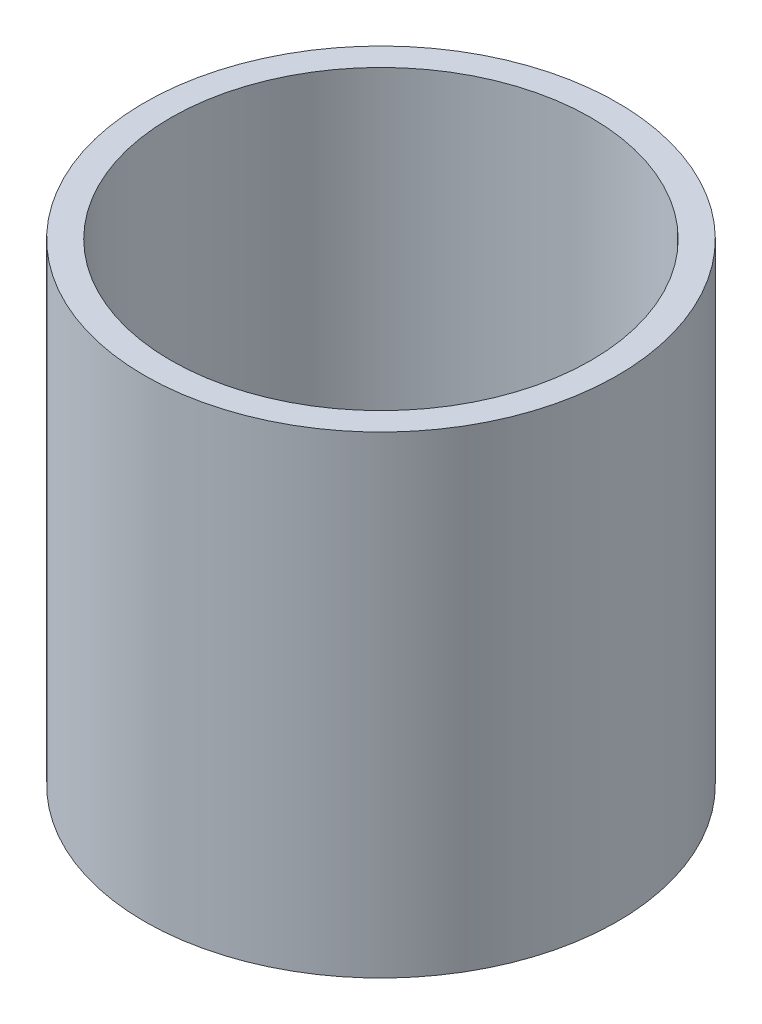
SolidWorks part; units mm, degrees
ref_plane "Front Plane" through (0, 0, 0) normal (0, 0, 1) x (1, 0, 0)
ref_plane "Top Plane" through (0, 0, 0) normal (0, 1, 0) x (1, 0, 0)
ref_plane "Right Plane" through (0, 0, 0) normal (1, 0, 0) x (0, 0, -1)
sketch "Sketch1" plane through (0, 0, 0) normal (0, 1, 0) x (1, 0, 0)
  circle A0 centre (0, 0) radius 0.889
  circle A1 centre (0, 0) radius 1
  dimension "D1" = 1.778
  dimension "D2" = 2
extrude "Boss-Extrude1" add sketch "Sketch1" along normal blind 2
